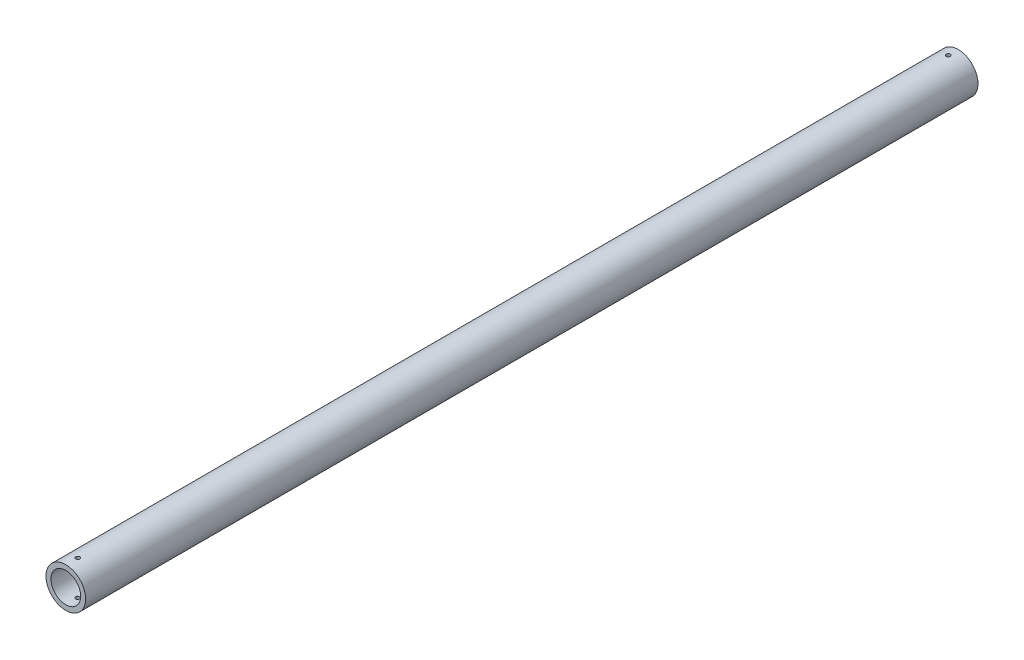
SolidWorks part; units mm, degrees
material "Литая нержавеющая сталь"
ref_plane "Спереди" through (0, 0, 0) normal (0, 0, 1) x (1, 0, 0)
ref_plane "Сверху" through (0, 0, 0) normal (0, 1, 0) x (1, 0, 0)
ref_plane "Справа" through (0, 0, 0) normal (1, 0, 0) x (0, 0, -1)
sketch "Эскиз1" plane through (0, 0, 0) normal (0, 0, 1) x (1, 0, 0)
  circle A0 centre (0, 0) radius 7.5
  circle A1 centre (0, 0) radius 10
  dimension "D1" = 15
  dimension "D2" = 20
extrude "Вытянуть1" add sketch "Эскиз1" along normal blind 450
sketch "Эскиз2" plane through (0, 0, 0) normal (0, 1, 0) x (1, 0, 0)
  circle A0 centre (0, -5) radius 1
  dimension "D1" = 2
  dimension "D2" = 5
extrude "Вытянуть2" cut sketch "Эскиз2" against normal mid plane 40
sketch "Эскиз3" plane through (0, 0, 0) normal (0, 1, 0) x (1, 0, 0)
  line L0 (-10, -450) -> (10, -450) construction
  circle A0 centre (0, -444) radius 1
  dimension "D1" = 6
  dimension "D2" = 2
extrude "Вытянуть3" cut sketch "Эскиз3" against normal mid plane 40
sketch "Эскиз5" plane through (0, 0, 0) normal (1, 0, 0) x (0, 0, -1)
  line L0 (0, 0) -> (7.2363, 0) construction
ref_plane "Плоскость1" through (0, 0, 225) normal (0, 0, 1) x (1, 0, 0)
